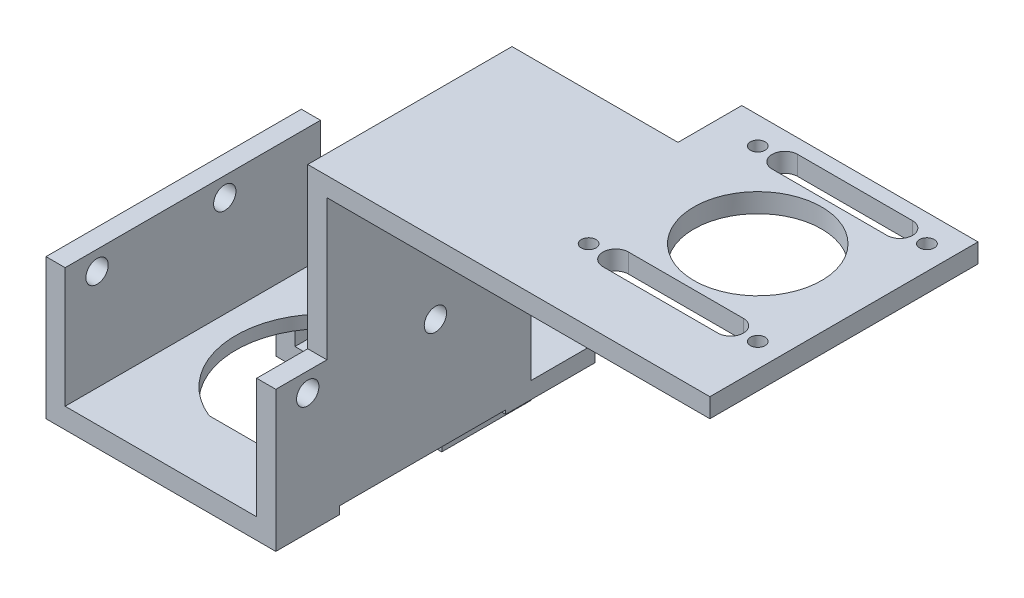
SolidWorks part; units mm, degrees
ref_plane "前视基准面" through (0, 0, 0) normal (0, 0, 1) x (1, 0, 0)
ref_plane "上视基准面" through (0, 0, 0) normal (0, 1, 0) x (1, 0, 0)
ref_plane "右视基准面" through (0, 0, 0) normal (1, 0, 0) x (0, 0, -1)
sketch "草图1" plane through (0, 0, 0) normal (0, 1, 0) x (1, 0, 0)
  line L1 (-18, 20) -> (18, 20)
  line L2 (-18, 20) -> (-18, -20)
  line L3 (-18, -20) -> (18, -20)
  line L4 (18, 20) -> (18, -20)
  line L5 (-18, 20) -> (18, -20) construction
  line L6 (-18, -20) -> (18, 20) construction
  point P0 (0, 0)
  dimension "D1" = 40
  dimension "D2" = 36
extrude "凸台-拉伸1" add sketch "草图1" along normal blind 3
ref_plane "基准面1" through (0, 3, 0) normal (0, 1, 0) x (1, 0, 0)
sketch "草图2" plane through (0, 3, 0) normal (0, 1, 0) x (1, 0, 0)
  line L0 (-18, -20) -> (18, -20) construction
  line L1 (-18, 20) -> (-15, 20)
  line L2 (-18, 20) -> (-18, -20)
  line L3 (-18, -20) -> (-15, -20)
  line L4 (-15, 20) -> (-15, -20)
  line L6 (18, 20) -> (15, 20)
  line L7 (18, 20) -> (18, -20)
  line L8 (18, -20) -> (15, -20)
  line L9 (15, 20) -> (15, -20)
  dimension "D1" = 3
  dimension "D2" = 3
extrude "凸台-拉伸2" add sketch "草图2" along normal blind 18.8
ref_plane "基准面2" through (0, 0, 0) normal (0, -1, 0) x (-1, 0, 0)
sketch "草图3" plane through (0, 0, 0) normal (0, -1, 0) x (-1, 0, 0)
  circle A0 centre (-2.75, 3) radius 14
  dimension "D1" = 28
extrude "切除-拉伸1" cut sketch "草图3" against normal blind 9
ref_plane "基准面3" through (0, 0, 20) normal (0, 0, 1) x (1, 0, 0)
sketch "草图4" plane through (0, 0, 20) normal (0, 0, 1) x (1, 0, 0)
  line L0 (18, 21.8) -> (18, 0) construction
  line L1 (-18, 0) -> (18, 0)
  line L2 (-18, 0) -> (-18, 3)
  line L3 (-18, 3) -> (18, 3)
  line L4 (18, 0) -> (18, 3)
  line L5 (16.5, 3) -> (-16.5, 3) construction
extrude "凸台-拉伸3" add sketch "草图4" along normal blind 10
sketch "草图6" plane through (0, 0, 0) normal (0, -1, 0) x (-1, 0, 0)
  circle A0 centre (-2.75, -16.15) radius 2.7
  dimension "D2" = 5.4
  dimension "D1" = 19.15
extrude "切除-拉伸3" cut sketch "草图6" against normal blind 10
ref_plane "基准面4" through (-18, 0, 0) normal (-1, 0, 0) x (0, 0, 1)
sketch "草图7" plane through (-18, 0, 0) normal (-1, 0, 0) x (0, 0, 1)
  line L0 (20, -1.65) -> (20, 1.65) construction
  line L2 (-20, 21.8) -> (20, 21.8) construction
  circle A0 centre (15, 18.8) radius 1.75
  circle A1 centre (-5, 18.8) radius 1.75
  dimension "D1" = 3.5
  dimension "D2" = 3.5
  dimension "D3" = 5
  dimension "D4" = 3
  dimension "D5" = 3
  dimension "D6" = 20
extrude "切除-拉伸4" cut sketch "草图7" against normal through all
ref_plane "基准面5" through (0, 0, 0) normal (0, -1, 0) x (-1, 0, 0)
ref_plane "基准面6" through (0, 0, 30) normal (0, 0, 1) x (1, 0, 0)
sketch "草图9" plane through (0, 0, 30) normal (0, 0, 1) x (1, 0, 0)
  line L0 (-18, 13.365) -> (-18, -13.365) construction
  line L1 (-18, 0) -> (-15, 0)
  line L2 (-18, 0) -> (-18, -9.3)
  line L3 (-18, -9.3) -> (-15, -9.3)
  line L4 (-15, 0) -> (-15, -9.3)
  line L5 (-18, 3) -> (-18, 0) construction
  line L6 (-55, 0) -> (55, 0) construction
  line L7 (-15, -9.3) -> (10, -9.3)
  line L8 (-15, -9.3) -> (-15, -6.3)
  line L9 (-15, -6.3) -> (10, -6.3)
  line L10 (10, -9.3) -> (10, -6.3)
  dimension "D1" = 3
  dimension "D2" = 9.3
  dimension "D3" = 3
  dimension "D4" = 25
extrude "凸台-拉伸4" add sketch "草图9" against normal blind 20 contours L7 L10 L9 L4 | L4 L1 L2 L3
chamfer "倒角1" distance 5 angle 45 1 edges at (10, -7.8, 30)
sketch "草图10" plane through (0, 0, 0) normal (0, 1, 0) x (1, 0, 0)
  circle A0 centre (2.75, -16.15) radius 2.7
extrude "切除-拉伸5" cut sketch "草图10" against normal blind 30
sketch "草图11" plane through (-18, 0, 0) normal (-1, 0, 0) x (0, 0, 1)
  line L1 (40.054, -18.0711) -> (0, -18.0711)
  line L2 (40.054, -18.0711) -> (40.054, 0)
  line L3 (40.054, 0) -> (0, 0)
  line L4 (0, -18.0711) -> (0, 0)
extrude "切除-拉伸6" cut sketch "草图11" against normal through all
sketch "草图12" plane through (0, 0, 0) normal (0, -1, 0) x (-1, 0, 0)
  line L0 (18, 20) -> (18, -30) construction
  line L1 (-18, -30) -> (18, -30)
  line L2 (-18, -30) -> (-18, -10)
  line L3 (-18, -10) -> (18, -10)
  line L4 (18, -30) -> (18, -10)
  circle A0 centre (-2.75, -16.15) radius 2.7
  dimension "D1" = 20
extrude "凸台-拉伸5" add sketch "草图12" along normal blind 2.5
sketch "草图13" plane through (0, 0, 0) normal (0, -1, 0) x (-1, 0, 0)
  line L1 (-30.9744, -10) -> (31.1483, -10)
  line L2 (-30.9744, -10) -> (-30.9744, 25.5614)
  line L3 (-30.9744, 25.5614) -> (31.1483, 25.5614)
  line L4 (31.1483, -10) -> (31.1483, 25.5614)
extrude "切除-拉伸7" cut sketch "草图13" against normal blind 1
ref_plane "基准面7" through (18, 0, 0) normal (1, 0, 0) x (0, 0, -1)
ref_plane "基准面8" through (0, 0, 20) normal (0, 0, 1) x (1, 0, 0)
sketch "草图16" plane through (0, 0, 20) normal (0, 0, 1) x (1, 0, 0)
  line L0 (18, -13.365) -> (18, 13.365) construction
  line L1 (15, 21.8) -> (18, 21.8)
  line L2 (15, 21.8) -> (15, 46.8)
  line L3 (15, 46.8) -> (18, 46.8)
  line L4 (18, 21.8) -> (18, 46.8)
  line L6 (18, 46.8) -> (78, 46.8)
  line L7 (18, 46.8) -> (18, 43.8)
  line L8 (18, 43.8) -> (78, 43.8)
  line L9 (78, 46.8) -> (78, 43.8)
  dimension "D1" = 25
  dimension "D2" = 60
  dimension "D3" = 3
extrude "凸台-拉伸7" add sketch "草图16" against normal blind 65 contours L9 L6 L4 L8 | L1 L4 L3 L2
ref_plane "基准面9" through (0, 9, 0) normal (0, -1, 0) x (-1, 0, 0)
sketch "草图17" plane through (0, 9, 0) normal (0, -1, 0) x (-1, 0, 0)
  line L0 (-15, 9.7777) -> (-15, -3.7777)
  circle A0 centre (-2.75, 3) radius 14
extrude "凸台-拉伸8" add sketch "草图17" along normal up to surface (8 mm away) contours L0 A0
ref_plane "基准面10" through (0, 46.8, 0) normal (0, 1, 0) x (1, 0, 0)
sketch "草图18" plane through (0, 46.8, 0) normal (0, 1, 0) x (1, 0, 0)
  line L0 (78, 45) -> (78, -20) construction
  line L1 (47.75, 25.75) -> (74.25, 25.75) construction
  line L2 (47.75, 25.75) -> (47.75, -0.75) construction
  line L3 (47.75, -0.75) -> (74.25, -0.75) construction
  line L4 (74.25, 25.75) -> (74.25, -0.75) construction
  line L5 (47.75, 25.75) -> (74.25, -0.75) construction
  line L6 (47.75, -0.75) -> (74.25, 25.75) construction
  line L7 (52, 25.75) -> (70, 25.75) construction
  line L8 (52, 27.75) -> (70, 27.75)
  line L9 (52, 23.75) -> (70, 23.75)
  line L10 (47.75, 12.5) -> (74.25, 12.5) construction
  line L11 (52, -0.75) -> (70, -0.75) construction
  line L12 (52, -2.75) -> (70, -2.75)
  line L13 (52, 1.25) -> (70, 1.25)
  line L14 (15, 12.5) -> (78, 12.5) construction
  line L15 (15, 45) -> (15, -20) construction
  circle A0 centre (47.75, 25.75) radius 1.15
  circle A1 centre (74.25, 25.75) radius 1.15
  circle A2 centre (74.25, -0.75) radius 1.15
  circle A3 centre (47.75, -0.75) radius 1.15
  circle A4 centre (61, 12.5) radius 10
  arc A5 (52, 27.75) -> (52, 23.75) centre (52, 25.75) ccw
  arc A6 (70, 23.75) -> (70, 27.75) centre (70, 25.75) ccw
  arc A7 (52, -2.75) -> (52, 1.25) centre (52, -0.75) cw
  arc A8 (70, 1.25) -> (70, -2.75) centre (70, -0.75) cw
  point P0 (61, 12.5)
  point P15 (61, 25.75)
  point P24 (61, -0.75)
  dimension "D3" = 2.3
  dimension "D4" = 2.3
  dimension "D5" = 2.3
  dimension "D6" = 2.3
  dimension "D8" = 20
  dimension "D10" = 2
  dimension "D1" = 26.5
  dimension "D2" = 26.5
  dimension "D7" = 17
  dimension "D9" = 18
extrude "切除-拉伸8" cut sketch "草图18" against normal blind 15
ref_plane "基准面11" through (0, -2.5, 0) normal (0, -1, 0) x (-1, 0, 0)
sketch "草图19" plane through (0, -2.5, 0) normal (0, -1, 0) x (-1, 0, 0)
  line L1 (-57.3424, 35.7643) -> (67.8869, 35.7643)
  line L2 (-57.3424, 35.7643) -> (-57.3424, -68.1586)
  line L3 (-57.3424, -68.1586) -> (67.8869, -68.1586)
  line L4 (67.8869, 35.7643) -> (67.8869, -68.1586)
extrude "切除-拉伸9" cut sketch "草图19" against normal blind 0.5
ref_plane "基准面12" through (0, -2, 0) normal (0, -1, 0) x (-1, 0, 0)
sketch "草图20" plane through (0, -2, 0) normal (0, -1, 0) x (-1, 0, 0)
  line L1 (-74.5179, 37.5036) -> (80.2794, 37.5036)
  line L2 (-74.5179, 37.5036) -> (-74.5179, -52.9398)
  line L3 (-74.5179, -52.9398) -> (80.2794, -52.9398)
  line L4 (80.2794, 37.5036) -> (80.2794, -52.9398)
extrude "切除-拉伸10" cut sketch "草图20" against normal blind 1.8
ref_plane "基准面13" through (0, 0, 0) normal (0, 1, 0) x (1, 0, 0)
sketch "草图21" plane through (0, 0, 0) normal (0, 1, 0) x (1, 0, 0)
  line L1 (-2.4461, -10) -> (8.7096, -10)
  line L2 (-2.4461, -10) -> (-2.4461, -12.6038)
  line L3 (-2.4461, -12.6038) -> (8.7096, -12.6038)
  line L4 (8.7096, -10) -> (8.7096, -12.6038)
extrude "凸台-拉伸9" add sketch "草图21" along normal up to surface (3 mm away) up to face at (2.75, 3, 18.85)
ref_plane "基准面14" through (0, 0, -20) normal (0, 0, -1) x (-1, 0, 0)
sketch "草图22" plane through (0, 0, -20) normal (0, 0, -1) x (-1, 0, 0)
  line L0 (18, -13.365) -> (18, 13.365) construction
  line L1 (18, 3) -> (-18, 3)
  line L2 (18, 3) -> (18, -0.2)
  line L3 (18, -0.2) -> (-18, -0.2)
  line L4 (-18, 3) -> (-18, -0.2)
  line L5 (18, 3) -> (18, -0.2) construction
  line L6 (-18, 21.8) -> (-18, 1) construction
  line L7 (-15, 3) -> (15, 3) construction
  dimension "D1" = 3.2
extrude "凸台-拉伸10" add sketch "草图22" along normal blind 10 and the other way blind 4
sketch "草图23" plane through (0, 9, 0) normal (0, -1, 0) x (-1, 0, 0)
  circle A0 centre (-2.75, 22.15) radius 1.75
  arc A1 (2.4461, -10) -> (2.4462, 16) centre (-2.75, 3) ccw construction
  dimension "D1" = 19.15
  dimension "D2" = 3.5
extrude "切除-拉伸12" cut sketch "草图23" along normal blind 10
sketch "草图26" plane through (0, 3, 0) normal (0, 1, 0) x (1, 0, 0)
  line L1 (-3.0023, -13.2404) -> (9.8436, -13.2404)
  line L2 (-3.0023, -13.2404) -> (-3.0023, -20.6177)
  line L3 (-3.0023, -20.6177) -> (9.8436, -20.6177)
  line L4 (9.8436, -13.2404) -> (9.8436, -20.6177)
extrude "凸台-拉伸11" add sketch "草图26" against normal through all
sketch "草图27" plane through (0, 0, 30) normal (0, 0, 1) x (1, 0, 0)
  line L1 (-53.429, 28.6042) -> (62.9951, 28.6042)
  line L2 (-53.429, 28.6042) -> (-53.429, -33.9017)
  line L3 (-53.429, -33.9017) -> (62.9951, -33.9017)
  line L4 (62.9951, 28.6042) -> (62.9951, -33.9017)
extrude "切除-拉伸13" cut sketch "草图27" against normal blind 10
ref_plane "基准面16" through (0, 46.8, 0) normal (0, 1, 0) x (1, 0, 0)
sketch "草图29" plane through (0, 46.8, 0) normal (0, 1, 0) x (1, 0, 0)
  line L0 (-1.65, -20) -> (1.65, -20) construction
  line L1 (88.2149, 37) -> (-1.5762, 37)
  line L2 (88.2149, 37) -> (88.2149, 49.2847)
  line L3 (88.2149, 49.2847) -> (-1.5762, 49.2847)
  line L4 (-1.5762, 37) -> (-1.5762, 49.2847)
  line L5 (110.1735, -41.7854) -> (2.772, -41.7854)
  line L6 (110.1735, -41.7854) -> (110.1735, -12)
  line L7 (110.1735, -12) -> (2.772, -12)
  line L8 (2.772, -41.7854) -> (2.772, -12)
  line L9 (15, 45) -> (78, 45) construction
  dimension "D1" = 8
  dimension "D2" = 8
extrude "切除-拉伸14" cut sketch "草图29" against normal blind 25
ref_plane "基准面17" through (0, 0, -20) normal (0, 0, -1) x (-1, 0, 0)
sketch "草图30" plane through (0, 0, -20) normal (0, 0, -1) x (-1, 0, 0)
  line L0 (19.8, 3) -> (-19.8, 3) construction
  line L1 (-18, 21.8) -> (-15, 21.8)
  line L2 (-18, 21.8) -> (-18, 3)
  line L3 (-18, 3) -> (-15, 3)
  line L4 (-15, 21.8) -> (-15, 3)
  line L5 (18, 3) -> (-18, 3) construction
extrude "凸台-拉伸12" add sketch "草图30" along normal up to surface (17 mm away) up to face at (37, 37.4667, -37)
ref_plane "基准面18" through (0, -0.2, 0) normal (0, -1, 0) x (-1, 0, 0)
sketch "草图31" plane through (0, -0.2, 0) normal (0, -1, 0) x (-1, 0, 0)
  line L1 (-43.7541, 52.6137) -> (37.0144, 52.6137)
  line L2 (-43.7541, 52.6137) -> (-43.7541, 6.8485)
  line L3 (-43.7541, 6.8485) -> (37.0144, 6.8485)
  line L4 (37.0144, 52.6137) -> (37.0144, 6.8485)
extrude "切除-拉伸15" cut sketch "草图31" against normal blind 0.6
ref_plane "基准面19" through (0, 0, -30) normal (0, 0, -1) x (-1, 0, 0)
sketch "草图32" plane through (0, 0, -30) normal (0, 0, -1) x (-1, 0, 0)
  line L0 (15, 21.8) -> (15, 3) construction
  line L1 (15, 3) -> (18, 3)
  line L2 (15, 3) -> (15, -9.7)
  line L3 (15, -9.7) -> (18, -9.7)
  line L4 (18, 3) -> (18, -9.7)
  line L5 (15, 3) -> (18, 3) construction
  line L6 (18, -13.365) -> (18, 13.365) construction
  line L7 (-55, -0.2) -> (55, -0.2) construction
  line L8 (18, -9.7) -> (-8, -9.7)
  line L9 (18, -9.7) -> (18, -6.9)
  line L10 (18, -6.9) -> (-8, -6.9)
  line L11 (-8, -9.7) -> (-8, -6.9)
  dimension "D1" = 6.7
  dimension "D2" = 26
  dimension "D3" = 12.7
extrude "凸台-拉伸13" add sketch "草图32" against normal up to surface (14 mm away) contours L11 L8 L2 L10 | L10 L4 L1 L2 | L4 L10 L2 L3 up to face at (1.375, 1.35, -16)
sketch "草图34" plane through (0, 3, 0) normal (0, 1, 0) x (1, 0, 0)
  circle A0 centre (2.75, 22.15) radius 1.75
  dimension "D1" = 3.5
extrude "切除-拉伸17" cut sketch "草图34" against normal through all
ref_plane "基准面20" through (0, 0, -37) normal (0, 0, -1) x (-1, 0, 0)
sketch "草图35" plane through (0, 0, -37) normal (0, 0, -1) x (-1, 0, 0)
  line L1 (69.9523, -61.8537) -> (-98.7594, -61.8537)
  line L2 (69.9523, -61.8537) -> (69.9523, 67.0716)
  line L3 (69.9523, 67.0716) -> (-98.7594, 67.0716)
  line L4 (-98.7594, -61.8537) -> (-98.7594, 67.0716)
extrude "切除-拉伸18" cut sketch "草图35" against normal up to surface (7 mm away) up to face at (0.1111, -2.6, -30)
sketch "草图36" plane through (0, 46.8, 0) normal (0, 1, 0) x (1, 0, 0)
  line L0 (78, 30) -> (15, 30) construction
  line L1 (41, 20) -> (10.219, 20)
  line L2 (41, 20) -> (41, 40.3835)
  line L3 (41, 40.3835) -> (10.219, 40.3835)
  line L4 (10.219, 20) -> (10.219, 40.3835)
  line L5 (15, 30) -> (15, 9.7777) construction
  dimension "D1" = 10
  dimension "D2" = 26
extrude "切除-拉伸19" cut sketch "草图36" against normal up to surface (43.8 mm away) up to face at (-0.2273, 3, -6.5)
